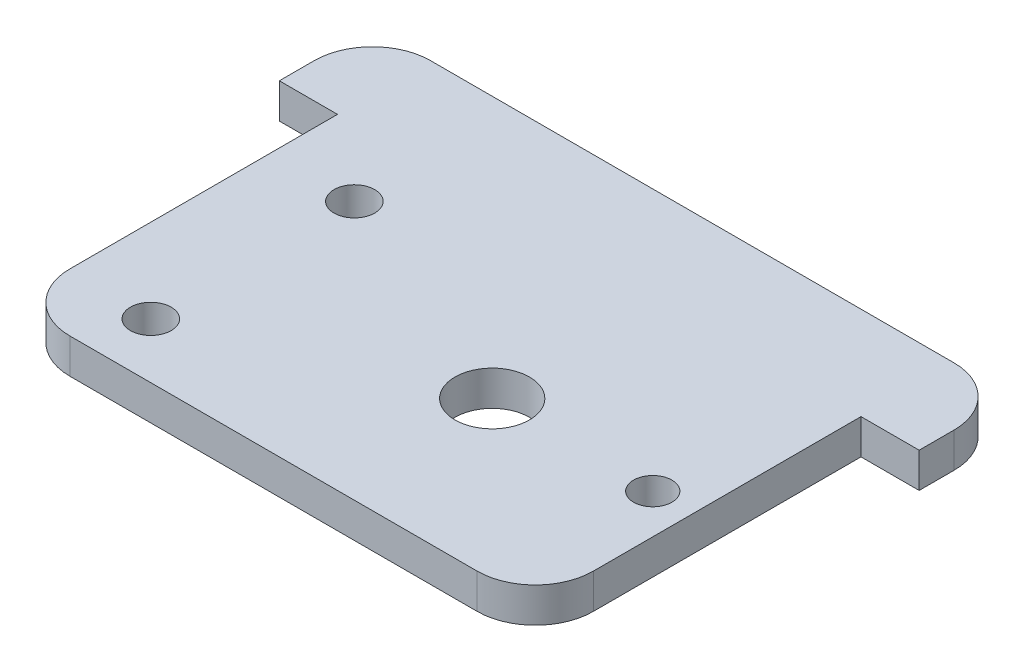
SolidWorks part; units mm, degrees
ref_plane "Front Plane" through (0, 0, 0) normal (0, 0, 1) x (1, 0, 0)
ref_plane "Top Plane" through (0, 0, 0) normal (0, 1, 0) x (1, 0, 0)
ref_plane "Right Plane" through (0, 0, 0) normal (1, 0, 0) x (0, 0, -1)
sketch "Sketch1" plane through (0, 0, 0) normal (0, 1, 0) x (1, 0, 0)
  line L0 (19.1, -0.5) -> (-22.5, -0.5) construction
  line L1 (-22.5, -14) -> (22.5, -14)
  line L2 (-22.5, -14) -> (-22.5, 14)
  line L3 (-22.5, 14) -> (22.5, 14)
  line L4 (22.5, -14) -> (22.5, 14)
  line L5 (-22.5, -14) -> (22.5, 14) construction
  line L6 (-22.5, 14) -> (22.5, -14) construction
  line L8 (-27.5, 14) -> (27.5, 14)
  line L9 (-27.5, 14) -> (-27.5, 22)
  line L10 (-27.5, 22) -> (27.5, 22)
  line L11 (27.5, 14) -> (27.5, 22)
  line L12 (-27.5, 14) -> (27.5, 22) construction
  line L13 (-27.5, 22) -> (27.5, 14) construction
  circle A0 centre (-15.3, -9.25) radius 1.75
  circle A1 centre (-15.3, 8.25) radius 1.75
  circle A2 centre (5.3, -0.5) radius 3.2
  circle A3 centre (19.1, -0.5) radius 1.65
  point P0 (0, 0)
  point P14 (0, 14)
  point P18 (0, 18)
  dimension "D3" = 3.5
  dimension "D4" = 3.5
  dimension "D5" = 6.4
  dimension "D6" = 3.3
  dimension "D1" = 45
  dimension "D2" = 28
  dimension "D7" = 8.75
  dimension "D8" = 8.75
  dimension "D9" = 7.2
  dimension "D10" = 20.6
  dimension "D11" = 13.8
  dimension "D12" = 4.75
  dimension "D13" = 5
  dimension "D14" = 8
extrude "Boss-Extrude1" add sketch "Sketch1" along normal blind 3 contours L8 L11 L10 L9 L3 | L1 L4 L3 L2 A3 A2 A1 A0
fillet "Fillet1" radius 5 4 edges at (22.5, 1.5, 14) (-22.5, 1.5, 14) (-27.5, 1.5, -22) (27.5, 1.5, -22)
